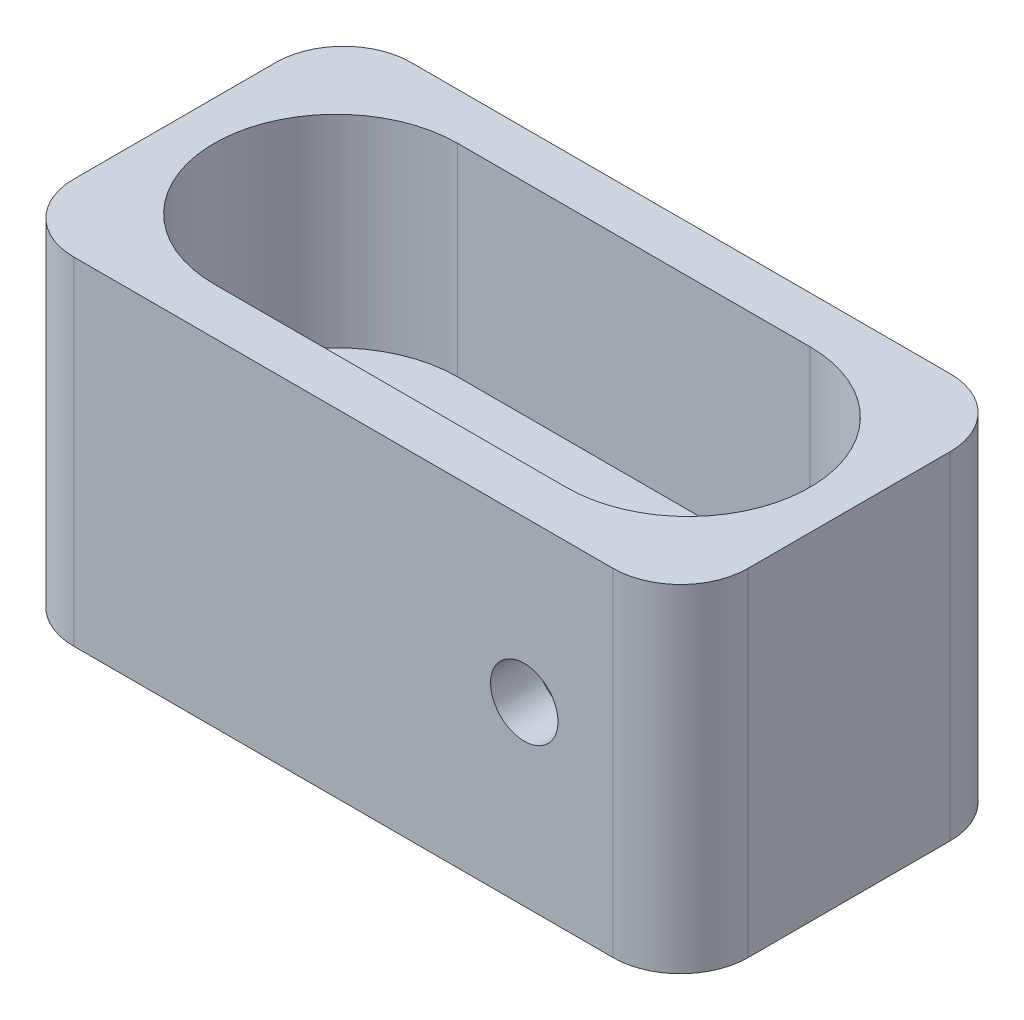
SolidWorks part; units mm, degrees
ref_plane "Front Plane" through (0, 0, 0) normal (0, 0, 1) x (1, 0, 0)
ref_plane "Top Plane" through (0, 0, 0) normal (0, 1, 0) x (1, 0, 0)
ref_plane "Right Plane" through (0, 0, 0) normal (1, 0, 0) x (0, 0, -1)
sketch "Sketch1" plane through (0, 0, 0) normal (0, 1, 0) x (1, 0, 0)
  line L1 (-25, -12.5) -> (25, -12.5)
  line L2 (-25, -12.5) -> (-25, 12.5)
  line L3 (-25, 12.5) -> (25, 12.5)
  line L4 (25, -12.5) -> (25, 12.5)
  line L5 (-25, -12.5) -> (25, 12.5) construction
  line L6 (-25, 12.5) -> (25, -12.5) construction
  point P0 (0, 0)
  dimension "D1" = 25
  dimension "D2" = 50
extrude "Boss-Extrude1" add sketch "Sketch1" along normal blind 25
fillet "Fillet2" radius 5 4 edges at (25, 12.5, -12.5) (25, 12.5, 12.5) (-25, 12.5, 12.5) (-25, 12.5, -12.5)
sketch "Sketch2" plane through (0, 25, 0) normal (0, 1, 0) x (1, 0, 0)
  line L0 (-13.0584, 0) -> (13.06, 0) construction
  line L7 (-13.0584, 9.0342) -> (13.06, 9.0342)
  line L8 (-13.0584, -9.0342) -> (13.06, -9.0342)
  arc A0 (-13.0584, 9.0342) -> (-13.0584, -9.0342) centre (-13.0584, 0) ccw
  arc A1 (13.06, -9.0342) -> (13.06, 9.0342) centre (13.06, 0) ccw
  point P0 (0, 0)
  point P1 (-22.0926, 0)
  point P5 (0.0008, 0)
  dimension "D1" = 26.1184
  dimension "D2" = 9.0342
extrude "Cut-Extrude1" cut sketch "Sketch2" against normal blind 15
sketch "Sketch3" plane through (0, 0, 12.5) normal (0, 0, 1) x (1, 0, 0)
  circle A0 centre (13.4084, 13.1058) radius 2.5
extrude "Cut-Extrude2" cut sketch "Sketch3" against normal blind 10
